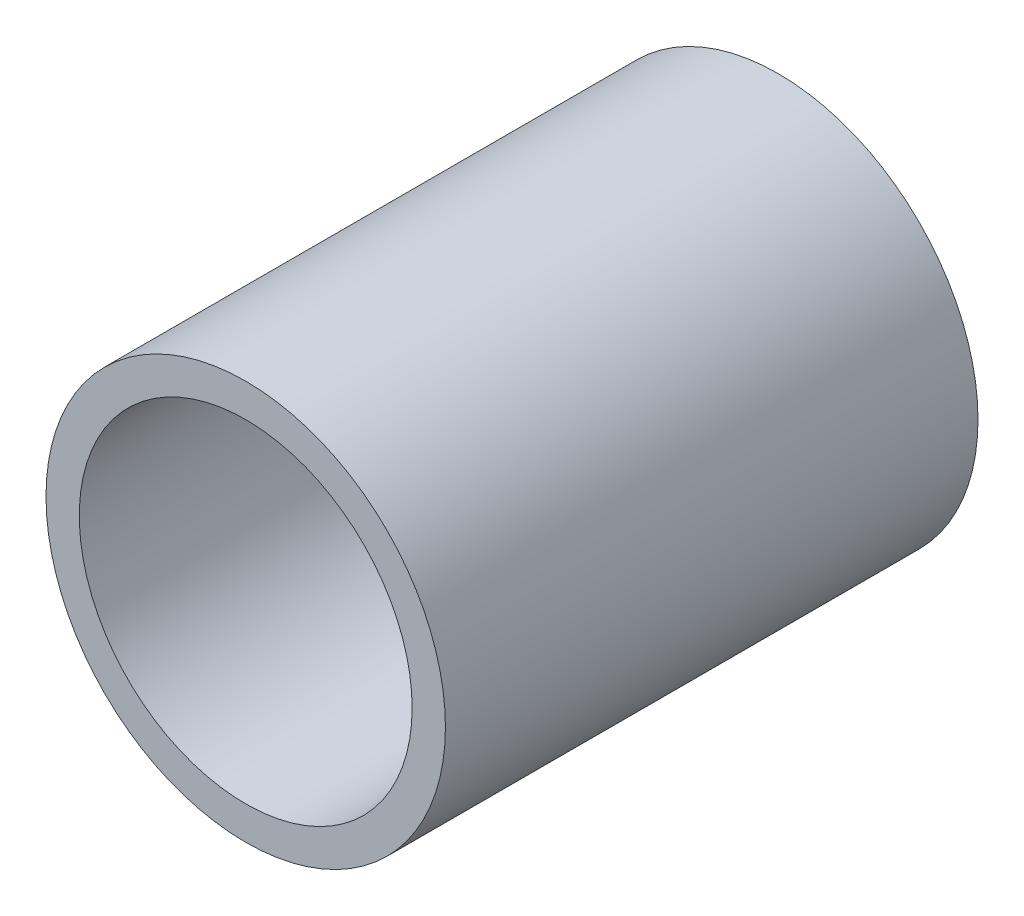
SolidWorks part; units mm, degrees
ref_plane "Front" through (0, 0, 0) normal (0, 0, 1) x (1, 0, 0)
ref_plane "Top" through (0, 0, 0) normal (0, 1, 0) x (1, 0, 0)
ref_plane "Right" through (0, 0, 0) normal (1, 0, 0) x (0, 0, -1)
sketch "Эскиз1" plane through (0, 0, 0) normal (0, 0, 1) x (1, 0, 0)
  circle A0 centre (0, 0) radius 15
  dimension "D1" = 30
extrude "Бобышка-Вытянуть1" add sketch "Эскиз1" along normal blind 40
sketch "Эскиз2" plane through (0, 0, 40) normal (0, 0, 1) x (1, 0, 0)
  circle A0 centre (0, 0) radius 12.5
  circle A1 centre (0, 0) radius 15 construction
  dimension "D1" = 2.5
extrude "Вырез-Вытянуть1" cut sketch "Эскиз2" against normal through all
